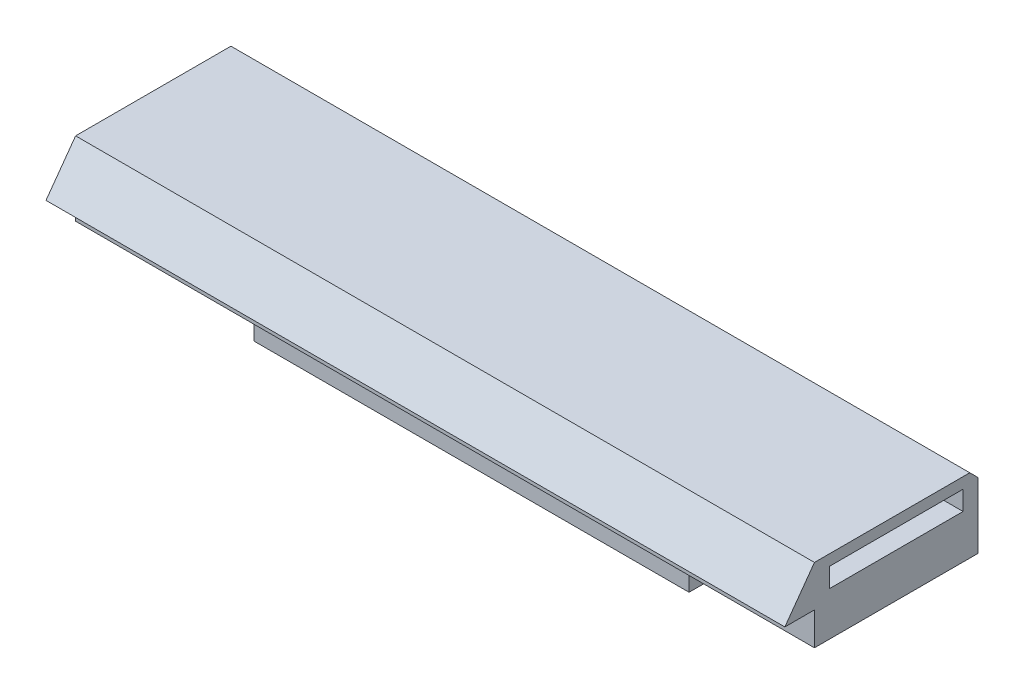
SolidWorks part; units mm, degrees
ref_plane "前视基准面" through (0, 0, 0) normal (0, 0, 1) x (1, 0, 0)
ref_plane "上视基准面" through (0, 0, 0) normal (0, 1, 0) x (1, 0, 0)
ref_plane "右视基准面" through (0, 0, 0) normal (1, 0, 0) x (0, 0, -1)
other "Configuration Table"
sketch "草图1" plane through (0, 0, 0) normal (0, 1, 0) x (1, 0, 0)
  line L1 (-4.495, -0.995) -> (4.495, -0.995)
  line L2 (-4.495, -0.995) -> (-4.495, 0.995)
  line L3 (-4.495, 0.995) -> (4.495, 0.995)
  line L4 (4.495, -0.995) -> (4.495, 0.995)
  line L5 (-4.495, -0.995) -> (4.495, 0.995) construction
  line L6 (-4.495, 0.995) -> (4.495, -0.995) construction
  point P0 (0, 0)
  dimension "D1" = 8.99
  dimension "D2" = 1.99
extrude "凸台-拉伸1" add sketch "草图1" along normal blind 1
sketch "草图2" plane through (4.495, 0, 0) normal (1, 0, 0) x (0, 0, -1)
  line L0 (-0.995, 0.5) -> (-1.355, 0.5)
  line L1 (-0.995, 1) -> (-0.995, 0) construction
  line L2 (-1.355, 0.5) -> (-0.995, 1)
  line L3 (-0.995, 1) -> (0.995, 1) construction
  line L4 (-0.995, 1) -> (-0.995, 0.5)
extrude "凸台-拉伸2" add sketch "草图2" against normal blind 8.99
sketch "草图3" plane through (4.495, 0, 0) normal (1, 0, 0) x (0, 0, -1)
  line L1 (-0.8135, 0.6325) -> (0.8135, 0.6325)
  line L2 (-0.8135, 0.6325) -> (-0.8135, 0.8675)
  line L3 (-0.8135, 0.8675) -> (0.8135, 0.8675)
  line L4 (0.8135, 0.6325) -> (0.8135, 0.8675)
  line L5 (-0.8135, 0.6325) -> (0.8135, 0.8675) construction
  line L6 (-0.8135, 0.8675) -> (0.8135, 0.6325) construction
  point P0 (0, 0.75)
extrude "切除-拉伸2" cut sketch "草图3" against normal blind 8.9
sketch "草图4" plane through (0, 0, 0) normal (0, -1, 0) x (1, 0, 0)
  line L1 (-2.6469, -0.6725) -> (2.6469, -0.6725)
  line L2 (-2.6469, -0.6725) -> (-2.6469, 0.6725)
  line L3 (-2.6469, 0.6725) -> (2.6469, 0.6725)
  line L4 (2.6469, -0.6725) -> (2.6469, 0.6725)
  line L5 (-2.6469, -0.6725) -> (2.6469, 0.6725) construction
  line L6 (-2.6469, 0.6725) -> (2.6469, -0.6725) construction
  point P0 (0, 0)
extrude "凸台-拉伸3" add sketch "草图4" along normal blind 0.5
sketch "草图5" plane through (0, 1, 0) normal (0, 1, 0) x (1, 0, 0)
  line L0 (4.495, 0.995) -> (-4.495, 0.995) construction
  line L1 (-2.3733, -0.995) -> (2.3733, -0.995)
  line L2 (-2.3733, -0.995) -> (-2.3733, 0.995)
  line L3 (-2.3733, 0.995) -> (2.3733, 0.995)
  line L4 (2.3733, -0.995) -> (2.3733, 0.995)
  line L5 (-2.3733, -0.995) -> (2.3733, 0.995) construction
  line L6 (-2.3733, 0.995) -> (2.3733, -0.995) construction
  point P0 (0, 0)
extrude "凸台-拉伸4" add sketch "草图5" against normal blind 0.5
chamfer "倒角1" distance 0.1 angle 45 12 edges at (0, -0.5, -0.6725) (-2.6469, -0.5, 0) (0, -0.5, 0.6725) (2.6469, -0.5, 0) (0, 0, -0.995) (-4.495, 0, 0) (0, 0, 0.995) (4.495, 0, 0) (0, 0, 0.6725) (-2.6469, 0, 0) (0, 0, -0.6725) (2.6469, 0, 0)
chamfer "倒角2" distance 0.1 angle 45 1 edges at (0, 1, -0.995)
